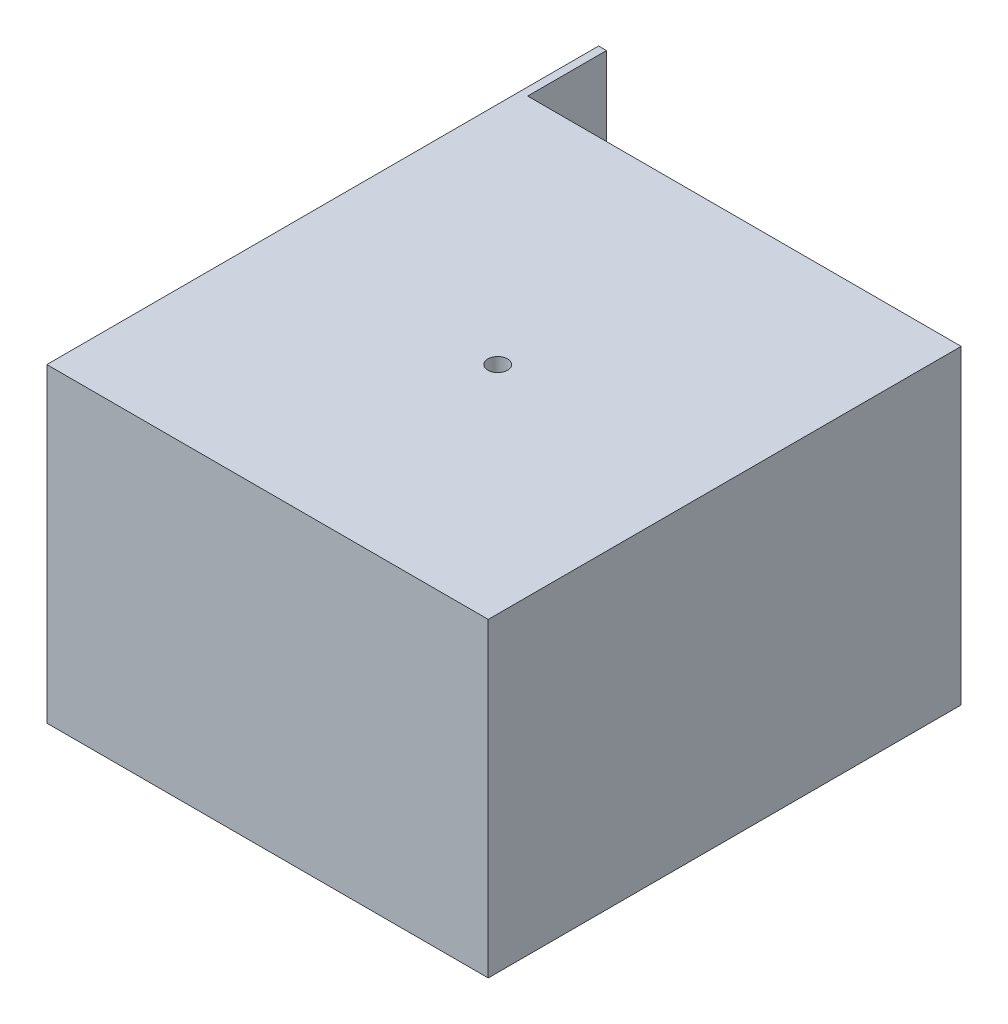
SolidWorks part; units mm, degrees
ref_plane "Front Plane" through (0, 0, 0) normal (0, 0, 1) x (1, 0, 0)
ref_plane "Top Plane" through (0, 0, 0) normal (0, 1, 0) x (1, 0, 0)
ref_plane "Right Plane" through (0, 0, 0) normal (1, 0, 0) x (0, 0, -1)
sketch "Sketch1" plane through (0, 0, 0) normal (0, 1, 0) x (1, 0, 0)
  line L1 (-35.56, -38.1) -> (35.56, -38.1)
  line L2 (-35.56, -38.1) -> (-35.56, 38.1)
  line L3 (-35.56, 38.1) -> (35.56, 38.1)
  line L4 (35.56, -38.1) -> (35.56, 38.1)
  line L5 (-35.56, -38.1) -> (35.56, 38.1) construction
  line L6 (-35.56, 38.1) -> (35.56, -38.1) construction
  point P0 (0, 0)
  dimension "D1" = 76.2
  dimension "D2" = 71.12
extrude "Boss-Extrude1" add sketch "Sketch1" along normal blind 50.038
sketch "Sketch2" plane through (0, 0, -38.1) normal (0, 0, -1) x (-1, 0, 0)
  line L0 (-35.56, 0) -> (35.56, 0) construction
  line L1 (35.56, 50.038) -> (34.29, 50.038)
  line L2 (35.56, 50.038) -> (35.56, 0)
  line L3 (35.56, 0) -> (34.29, 0)
  line L4 (34.29, 50.038) -> (34.29, 0)
  dimension "D1" = 1.27
extrude "Boss-Extrude2" add sketch "Sketch2" along normal blind 12.7
sketch "Sketch3" plane through (0, 0, 0) normal (0, -1, 0) x (1, 0, 0)
  line L0 (35.56, -38.1) -> (-34.29, -38.1) construction
  line L2 (-35.56, -50.8) -> (-35.56, 38.1) construction
  circle A0 centre (0.762, 1.778) radius 1.5875
  point P6 (2.3111, -7.9439)
  point P7 (-35.56, 3.3727)
  dimension "D1" = 39.878
  dimension "D3" = 3.175
  dimension "D2" = 36.322
extrude "Cut-Extrude1" cut sketch "Sketch3" against normal through all
